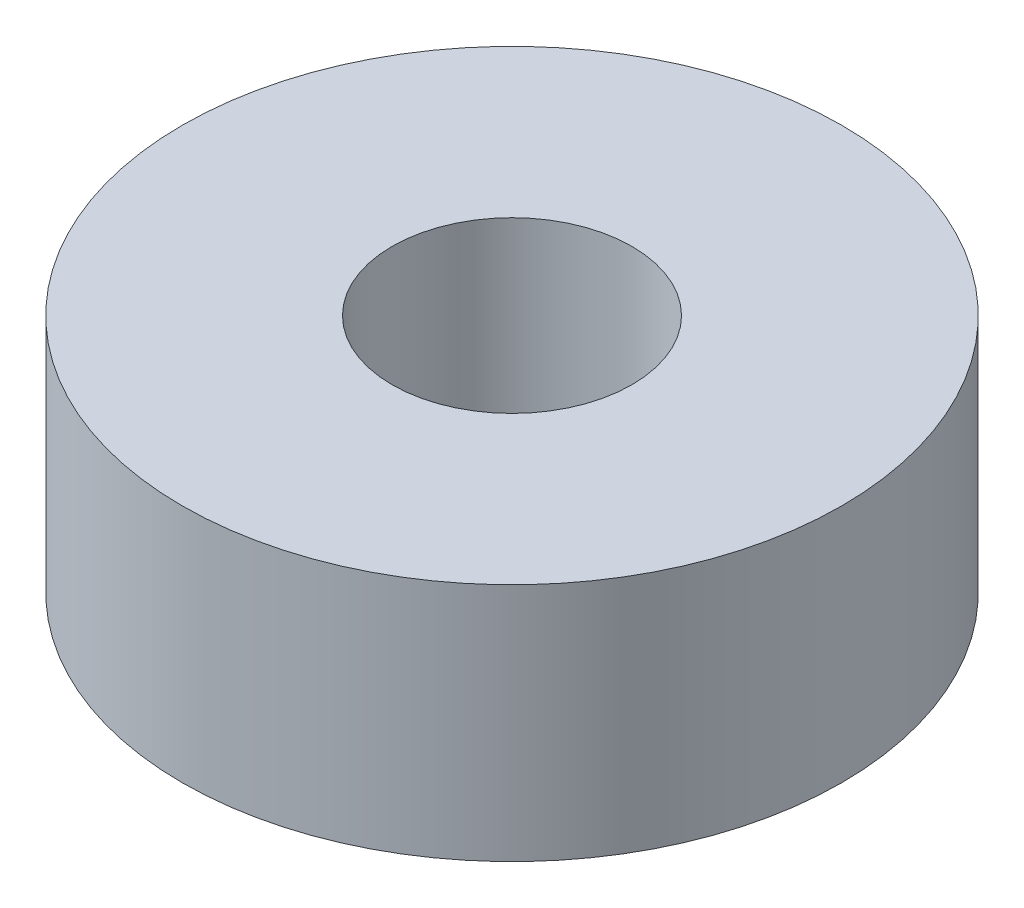
SolidWorks part; units mm, degrees
ref_plane "Спереди" through (0, 0, 0) normal (0, 0, 1) x (1, 0, 0)
ref_plane "Сверху" through (0, 0, 0) normal (0, 1, 0) x (1, 0, 0)
ref_plane "Справа" through (0, 0, 0) normal (1, 0, 0) x (0, 0, -1)
sketch "Эскиз1" plane through (0, 0, 0) normal (0, 1, 0) x (1, 0, 0)
  circle A0 centre (0, 0) radius 2
  circle A1 centre (0, 0) radius 5.5
  dimension "D1" = 4
  dimension "D2" = 11
extrude "Вытянуть1" add sketch "Эскиз1" along normal blind 4
